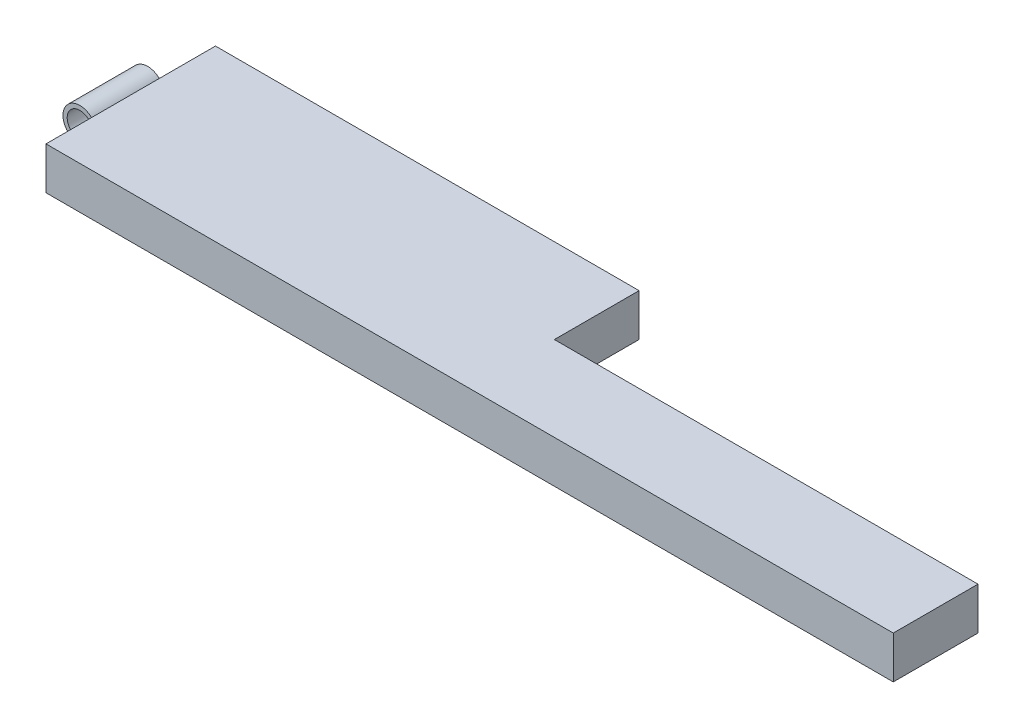
SolidWorks part; units mm, degrees
ref_plane "Front Plane" through (0, 0, 0) normal (0, 0, 1) x (1, 0, 0)
ref_plane "Top Plane" through (0, 0, 0) normal (0, 1, 0) x (1, 0, 0)
ref_plane "Right Plane" through (0, 0, 0) normal (1, 0, 0) x (0, 0, -1)
sketch "Sketch1" plane through (0, 0, 0) normal (0, 1, 0) x (1, 0, 0)
  line L0 (63.5, 25.4) -> (63.5, 12.7)
  line L1 (0, 0) -> (127, 0)
  line L2 (0, 0) -> (0, 25.4)
  line L3 (0, 25.4) -> (63.5, 25.4)
  line L4 (127, 0) -> (127, 12.7)
  line L5 (63.5, 12.7) -> (127, 12.7)
  dimension "D1" = 63.5
  dimension "D2" = 25.4
extrude "Boss-Extrude1" add sketch "Sketch1" along normal blind 6.35
ref_plane "Plane1" through (0, 0, -12.7) normal (0, 0, 1) x (1, 0, 0)
sketch "Sketch2" plane through (0, 0, -12.7) normal (0, 0, 1) x (1, 0, 0)
  line L0 (0, 6.35) -> (0, 0) construction
  circle A0 centre (-2.54, 3.7126) radius 2.54
  circle A1 centre (-2.54, 3.7126) radius 1.905
  dimension "D1" = 3.81
  dimension "D2" = 5.08
  dimension "D3" = 3.7126
extrude "Boss-Extrude2" add sketch "Sketch2" along normal blind 5.08 and the other way blind 5.08 separate body
